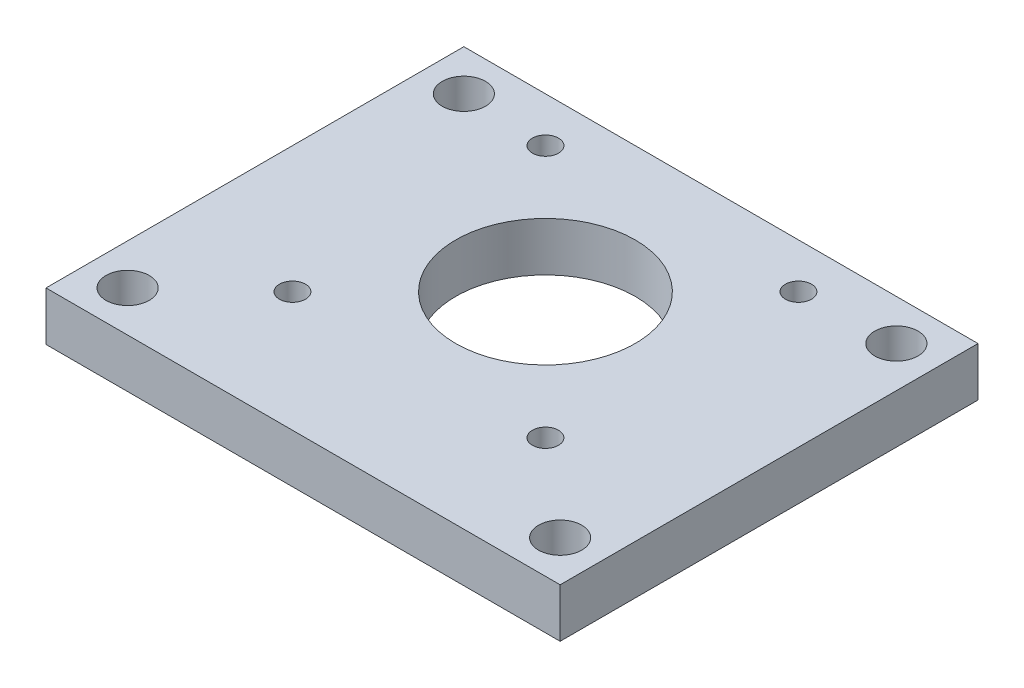
SolidWorks part; units mm, degrees
ref_plane "Front Plane" through (0, 0, 0) normal (0, 0, 1) x (1, 0, 0)
ref_plane "Top Plane" through (0, 0, 0) normal (0, 1, 0) x (1, 0, 0)
ref_plane "Right Plane" through (0, 0, 0) normal (1, 0, 0) x (0, 0, -1)
sketch "Sketch1" plane through (0, 0, 0) normal (0, 1, 0) x (1, 0, 0)
  line L0 (32, -30.2) -> (-31, -30.2)
  line L1 (15.5, -15.5) -> (-15.5, -15.5) construction
  line L2 (15.5, -15.5) -> (15.5, 15.5) construction
  line L3 (15.5, 15.5) -> (-15.5, 15.5) construction
  line L4 (-15.5, -15.5) -> (-15.5, 15.5) construction
  line L5 (15.5, -15.5) -> (-15.5, 15.5) construction
  line L6 (15.5, 15.5) -> (-15.5, -15.5) construction
  line L7 (-31, -30.2) -> (-31, 21)
  line L8 (-31, 21) -> (32, 21)
  line L9 (32, 21) -> (32, -30.2)
  line L10 (-21, 21) -> (-21, -30.2) construction
  circle A0 centre (0, 0) radius 11 construction
  circle A1 centre (-15.5, 15.5) radius 1.5 construction
  circle A2 centre (15.5, 15.5) radius 1.5 construction
  circle A3 centre (15.5, -15.5) radius 1.5 construction
  circle A4 centre (-15.5, -15.5) radius 1.5 construction
  circle A5 centre (27, -25.2) radius 5 construction
  circle A6 centre (27, -25.2) radius 2.5 construction
  circle A7 centre (-26, -25.2) radius 5 construction
  circle A8 centre (-26, -25.2) radius 2.5 construction
  circle A9 centre (27, 16) radius 5 construction
  circle A10 centre (27, 16) radius 2.5 construction
  circle A11 centre (-26, 16) radius 2.5 construction
  circle A12 centre (-26, 16) radius 5 construction
  point P3 (32, -30.2)
  dimension "D3" = 22
  dimension "D4" = 3
  dimension "D6" = 10
  dimension "D7" = 5
  dimension "D1" = 32
  dimension "D2" = 30.2
  dimension "D5" = 31
  dimension "D8" = 21
  dimension "D9" = 21
extrude "Boss-Extrude1" add sketch "Sketch1" along normal blind 6
hole_wizard "M5 Clearance Hole1" positions "Sketch2" profile "Sketch3" hole size "M5" standard "ANSI Metric" end condition through all
sketch "Sketch2" plane through (0, 6, 0) normal (0, 1, 0) x (1, 0, 0)
  point P0 (-26, 16)
  point P3 (-26, -25.2)
  point P6 (27, -25.2)
  point P9 (27, 16)
sketch "Sketch3" plane through (-26, 6, -16) normal (1, 0, 0) x (0, 0, 1)
  line L0 (0, 0) -> (0, 6)
  line L1 (0, 6) -> (2.65, 6)
  line L2 (2.65, 6) -> (2.65, 0)
  line L5 (2.65, 0) -> (0, 0)
  line L11 (0, -6.35) -> (0, 107.95) construction
  dimension "Thru Hole Dia." = 5.3
  dimension "Thru Hole Depth" = 6
hole_wizard "M3 Clearance Hole1" positions "Sketch4" profile "Sketch5" hole size "M3" standard "ANSI Metric" end condition through all
sketch "Sketch4" plane through (0, 6, 0) normal (0, 1, 0) x (1, 0, 0)
  point P0 (-15.5, 15.5)
  point P3 (15.5, 15.5)
  point P6 (15.5, -15.5)
  point P9 (-15.5, -15.5)
sketch "Sketch5" plane through (-15.5, 6, -15.5) normal (1, 0, 0) x (0, 0, 1)
  line L0 (0, 0) -> (0, 6)
  line L1 (0, 6) -> (1.6, 6)
  line L2 (1.6, 6) -> (1.6, 0)
  line L5 (1.6, 0) -> (0, 0)
  line L11 (0, -6.35) -> (0, 107.95) construction
  dimension "Thru Hole Dia." = 3.2
  dimension "Thru Hole Depth" = 6
hole_wizard "Ø22.0 (22) Diameter Hole1" positions "Sketch6" profile "Sketch7" hole size "Ø22.0" standard "ANSI Metric" end condition through all
sketch "Sketch6" plane through (0, 6, 0) normal (0, 1, 0) x (1, 0, 0)
  point P0 (0, 0)
sketch "Sketch7" plane through (0, 6, 0) normal (1, 0, 0) x (0, 0, 1)
  line L0 (0, 0) -> (0, 6)
  line L1 (0, 6) -> (11, 6)
  line L2 (11, 6) -> (11, 0)
  line L5 (11, 0) -> (0, 0)
  line L11 (0, -6.35) -> (0, 107.95) construction
  dimension "Thru Hole Dia." = 22
  dimension "Thru Hole Depth" = 6
